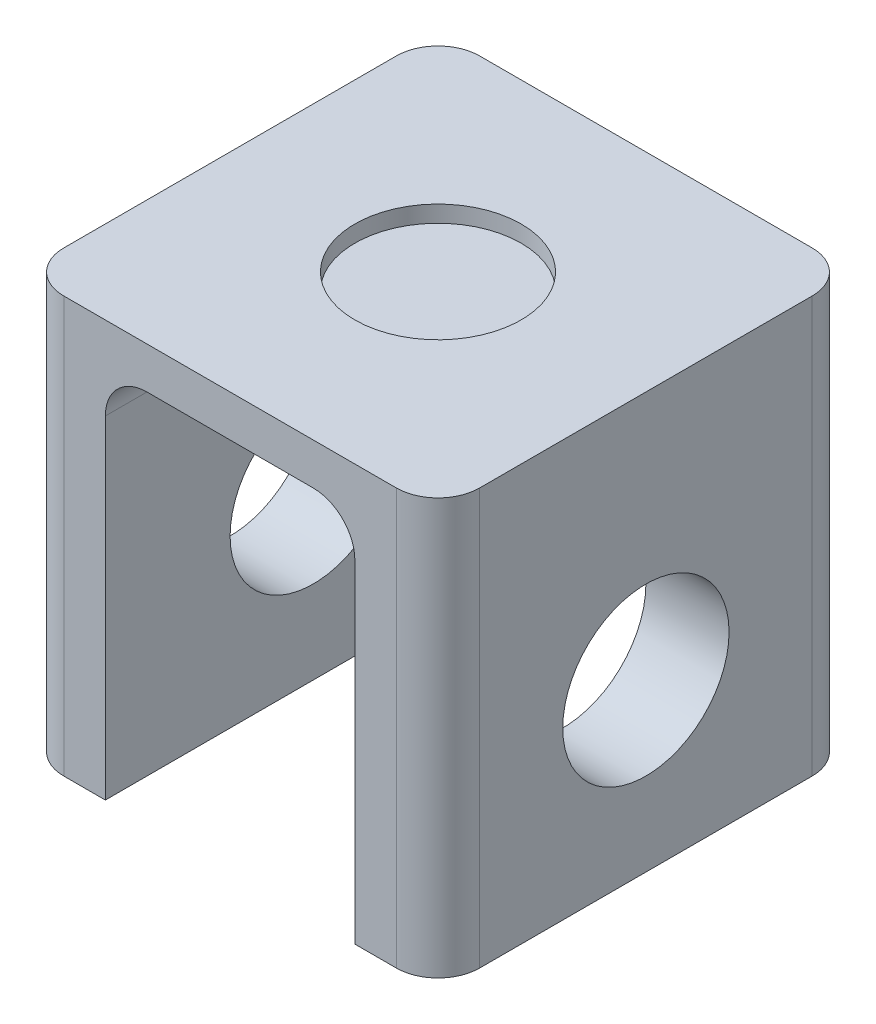
SolidWorks part; units mm, degrees
ref_plane "Front Plane" through (0, 0, 0) normal (0, 0, 1) x (1, 0, 0)
ref_plane "Top Plane" through (0, 0, 0) normal (0, 1, 0) x (1, 0, 0)
ref_plane "Right Plane" through (0, 0, 0) normal (1, 0, 0) x (0, 0, -1)
sketch "Sketch1" plane through (0, 0, 0) normal (0, 1, 0) x (1, 0, 0)
  line L1 (-50, -50) -> (50, -50)
  line L2 (-50, -50) -> (-50, 50)
  line L3 (-50, 50) -> (50, 50)
  line L4 (50, -50) -> (50, 50)
  line L5 (-50, -50) -> (50, 50) construction
  line L6 (-50, 50) -> (50, -50) construction
  point P0 (0, 0)
  dimension "D1" = 100
  dimension "D2" = 100
extrude "Boss-Extrude1" add sketch "Sketch1" along normal blind 100
sketch "Sketch2" plane through (0, 100, 0) normal (0, 1, 0) x (1, 0, 0)
  circle A0 centre (0, 0) radius 20
  dimension "D1" = 40
extrude "Cut-Extrude1" cut sketch "Sketch2" against normal blind 4
sketch "Sketch3" plane through (0, 0, 0) normal (0, -1, 0) x (1, 0, 0)
  line L1 (-30, -50) -> (30, -50)
  line L2 (-30, -50) -> (-30, 50)
  line L3 (-30, 50) -> (30, 50)
  line L4 (30, -50) -> (30, 50)
  line L5 (-30, -50) -> (30, 50) construction
  line L6 (-30, 50) -> (30, -50) construction
  point P0 (0, 0)
  dimension "D1" = 100
  dimension "D2" = 60
extrude "Cut-Extrude2" cut sketch "Sketch3" against normal blind 90
sketch "Sketch4" plane through (-50, 0, 0) normal (-1, 0, 0) x (0, 0, 1)
  line L0 (0, 100) -> (0, 40) construction
  line L1 (-50, 100) -> (50, 100) construction
  circle A1 centre (0, 40) radius 20
  dimension "D1" = 60
  dimension "D2" = 40
extrude "Cut-Extrude3" cut sketch "Sketch4" against normal blind 135
fillet "Fillet1" radius 10 4 edges at (-50, 50, -50) (-50, 50, 50) (50, 50, 50) (50, 50, -50)
fillet "Fillet2" radius 10 2 edges at (30, 90, 0) (-30, 90, 0)
